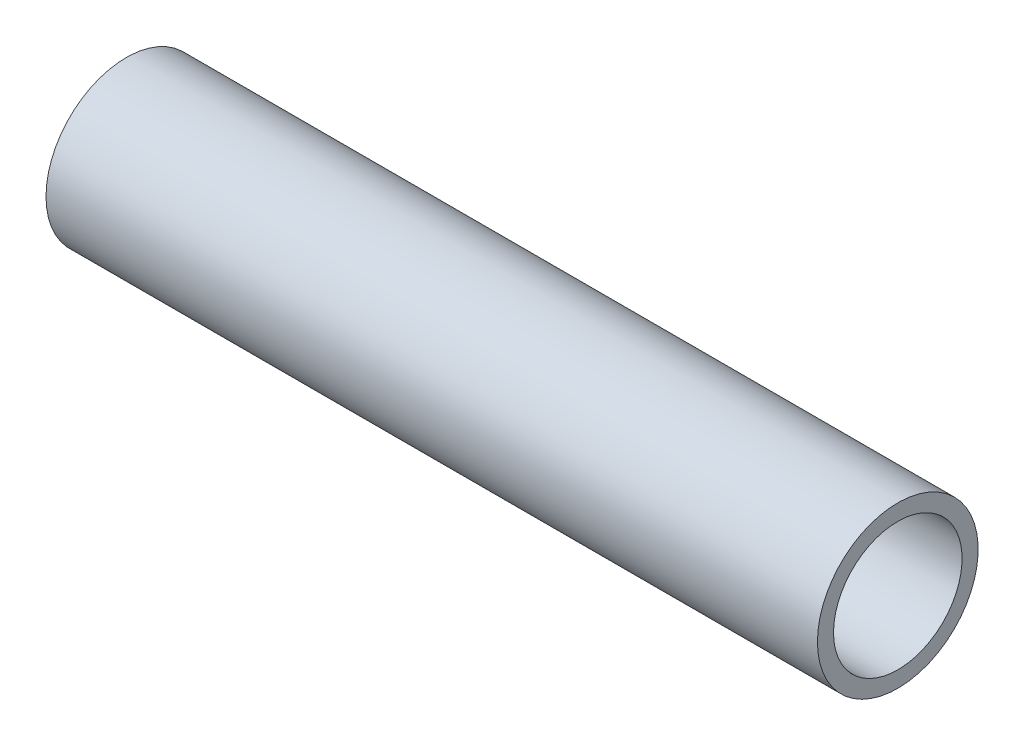
SolidWorks part; units mm, degrees
ref_plane "Front Plane" through (0, 0, 0) normal (0, 0, 1) x (1, 0, 0)
ref_plane "Top Plane" through (0, 0, 0) normal (0, 1, 0) x (1, 0, 0)
ref_plane "Right Plane" through (0, 0, 0) normal (1, 0, 0) x (0, 0, -1)
sketch "Sketch1" plane through (0, 0, 0) normal (1, 0, 0) x (0, 0, -1)
  circle A0 centre (0, 0) radius 6.35
  circle A1 centre (0, 0) radius 7.9375
extrude "Boss-Extrude1" add sketch "Sketch1" along normal blind 76.2
